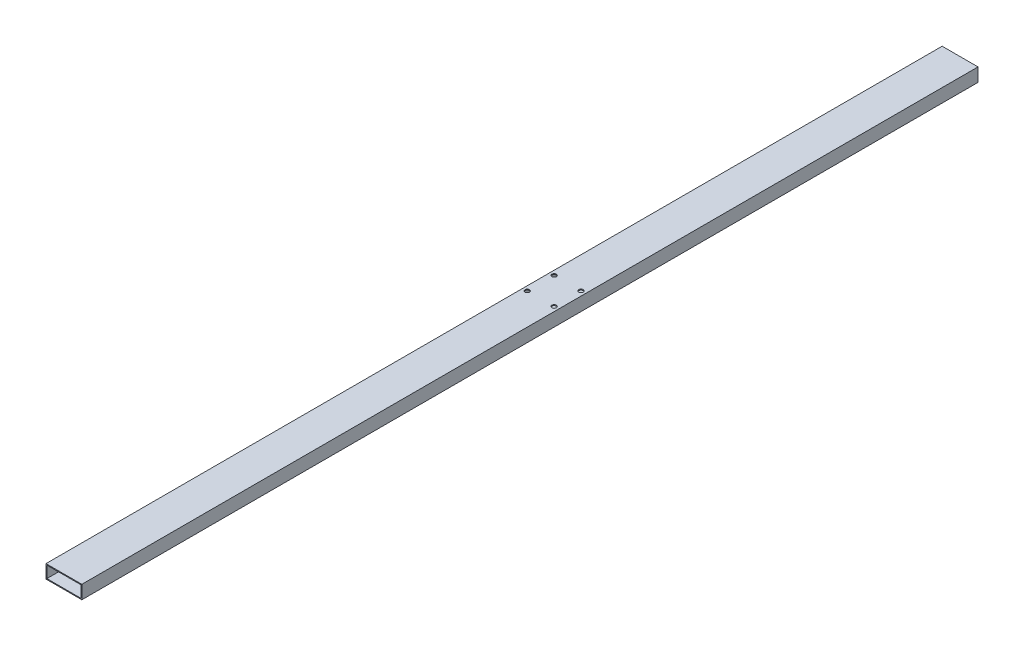
SolidWorks part; units mm, degrees
material "1060-H18 棒材(SS)"
ref_plane "前视基准面" through (0, 0, 0) normal (0, 0, 1) x (1, 0, 0)
ref_plane "上视基准面" through (0, 0, 0) normal (0, 1, 0) x (1, 0, 0)
ref_plane "右视基准面" through (0, 0, 0) normal (1, 0, 0) x (0, 0, -1)
other "Configuration Table"
sketch "草图1" plane through (0, 0, 0) normal (0, 0, 1) x (1, 0, 0)
  line L1 (0, 0) -> (40, 0)
  line L2 (0, 0) -> (0, 15)
  line L3 (0, 15) -> (40, 15)
  line L4 (40, 0) -> (40, 15)
  line L5 (1, 1) -> (39, 1)
  line L6 (1, 1) -> (1, 14)
  line L7 (1, 14) -> (39, 14)
  line L8 (39, 1) -> (39, 14)
  dimension "D1" = 40
  dimension "D2" = 15
  dimension "D3" = 1
  dimension "D4" = 1
  dimension "D5" = 1
  dimension "D6" = 1
extrude "凸台-拉伸1" add sketch "草图1" along normal blind 1000
sketch "草图3" plane through (0, 0, 0) normal (0, -1, 0) x (1, 0, 0)
  circle A1 centre (35, 468) radius 2.5
  circle A2 centre (35, 468) radius 2.5
  circle A3 centre (35, 438) radius 2.5
  circle A4 centre (35, 438) radius 2.5
  circle A5 centre (5, 468) radius 2.5
  circle A6 centre (5, 468) radius 2.5
  circle A7 centre (5, 438) radius 2.5
  circle A8 centre (5, 438) radius 2.5
  dimension "D1" = 0
  dimension "D2" = 0
  dimension "D3" = 0
  dimension "D4" = 0
extrude "切除-拉伸2" cut sketch "草图3" against normal through all
